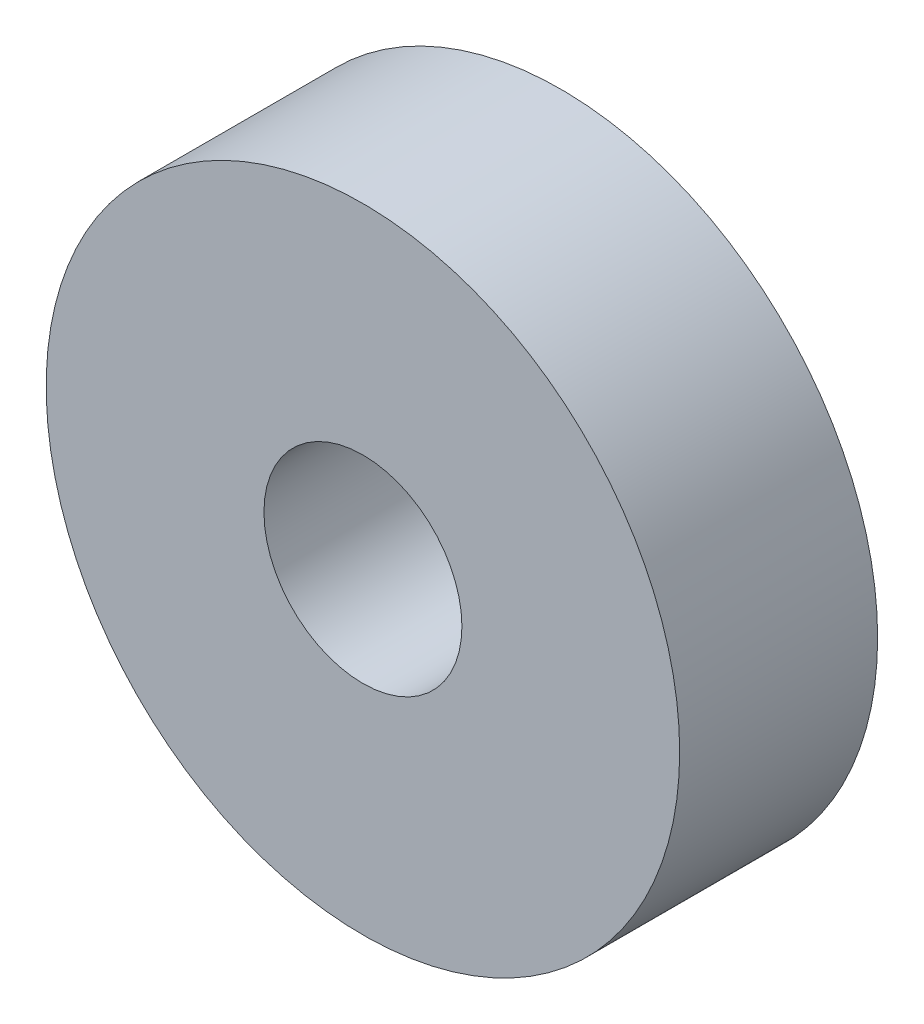
SolidWorks part; units mm, degrees
ref_plane "前视基准面" through (0, 0, 0) normal (0, 0, 1) x (1, 0, 0)
ref_plane "上视基准面" through (0, 0, 0) normal (0, 1, 0) x (1, 0, 0)
ref_plane "右视基准面" through (0, 0, 0) normal (1, 0, 0) x (0, 0, -1)
other "Configuration Table"
sketch "草图1" plane through (0, 0, 0) normal (0, 0, 1) x (1, 0, 0)
  circle A0 centre (0, 0) radius 8
  circle A1 centre (0, 0) radius 2.5
extrude "Purchased_625ZZ_5x16x5_NOT_PRINT" add sketch "草图1" along normal blind 5
